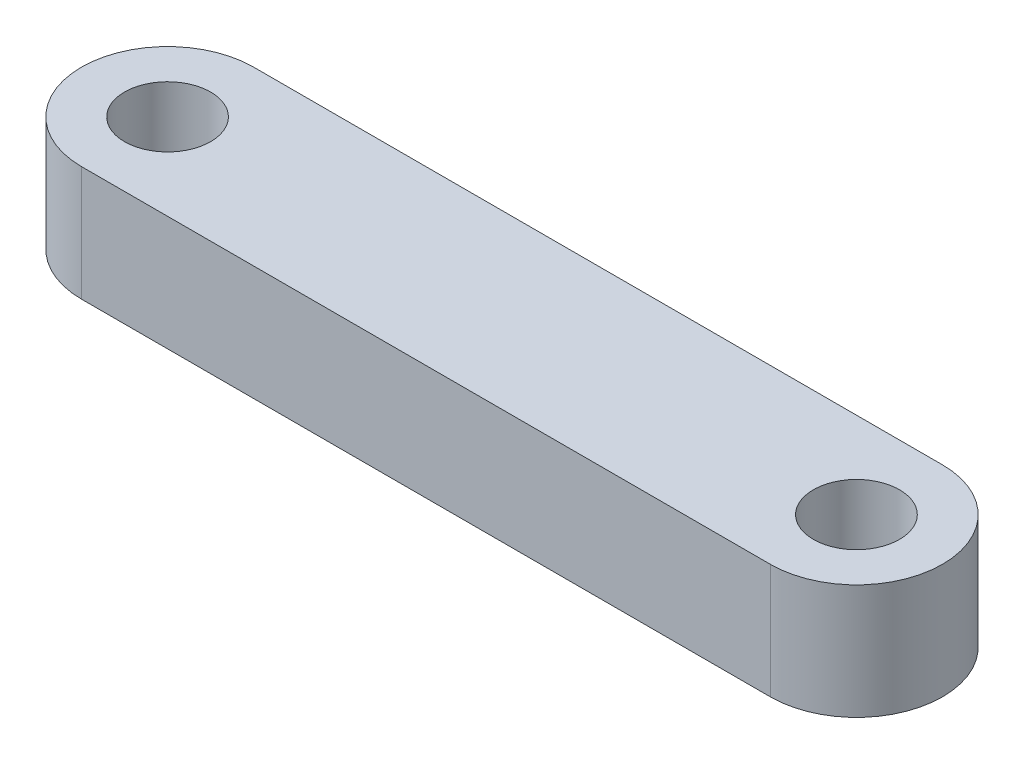
SolidWorks part; units mm, degrees
ref_plane "前视基准面" through (0, 0, 0) normal (0, 0, 1) x (1, 0, 0)
ref_plane "上视基准面" through (0, 0, 0) normal (0, 1, 0) x (1, 0, 0)
ref_plane "右视基准面" through (0, 0, 0) normal (1, 0, 0) x (0, 0, -1)
sketch "草图1" plane through (0, 0, 0) normal (0, 1, 0) x (1, 0, 0)
  line L0 (0, 0) -> (24, 0) construction
  line L1 (0, 3) -> (24, 3)
  line L2 (0, -3) -> (24, -3)
  arc A0 (0, 3) -> (0, -3) centre (0, 0) ccw
  arc A1 (24, -3) -> (24, 3) centre (24, 0) ccw
  circle A2 centre (0, 0) radius 1.5
  circle A3 centre (24, 0) radius 1.5
  point P3 (12, 0)
  dimension "D3" = 3
  dimension "D1" = 24
  dimension "D2" = 6
extrude "凸台-拉伸1" add sketch "草图1" along normal blind 4
